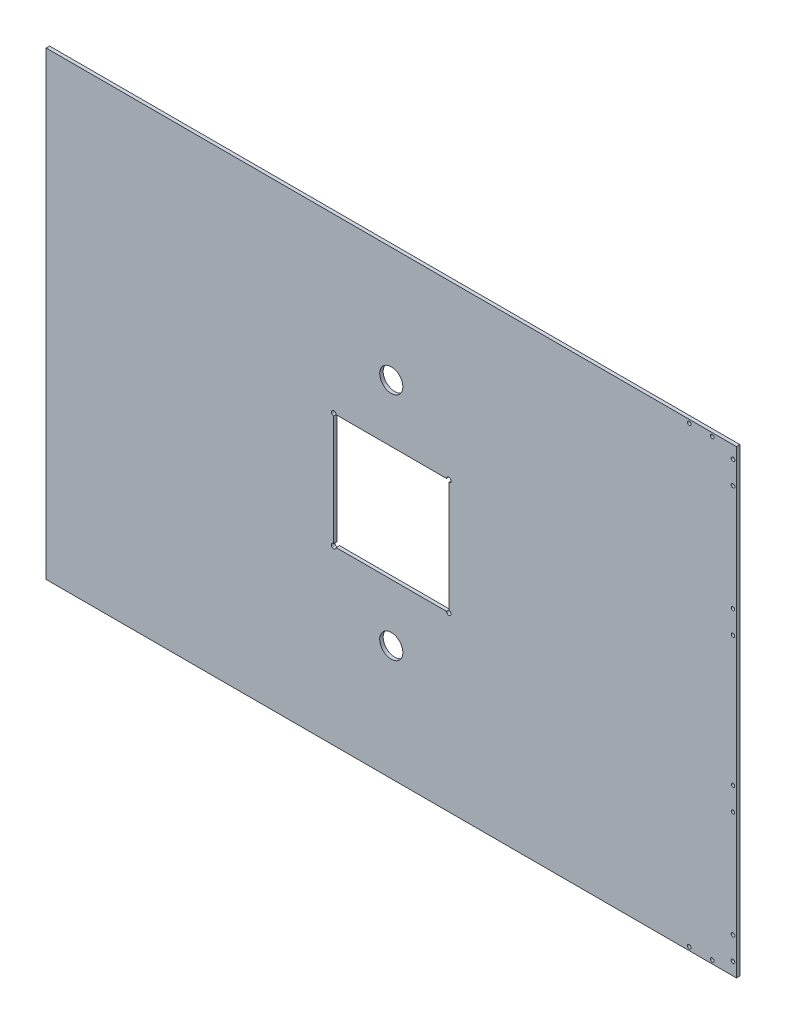
SolidWorks part; units mm, degrees
ref_plane "前视基准面" through (0, 0, 0) normal (0, 0, 1) x (1, 0, 0)
ref_plane "上视基准面" through (0, 0, 0) normal (0, 1, 0) x (1, 0, 0)
ref_plane "右视基准面" through (0, 0, 0) normal (1, 0, 0) x (0, 0, -1)
other "Configuration Table"
sketch "草图1" plane through (0, 0, 0) normal (0, 0, 1) x (1, 0, 0)
  line L1 (-300, 200) -> (300, 200)
  line L2 (-300, 200) -> (-300, -200)
  line L3 (-300, -200) -> (300, -200)
  line L4 (300, 200) -> (300, -200)
  line L5 (-300, 200) -> (300, -200) construction
  line L6 (-300, -200) -> (300, 200) construction
  point P0 (0, 0)
  dimension "D1" = 600
  dimension "D2" = 400
extrude "凸台-拉伸1" add sketch "草图1" along normal blind 3
sketch "草图3" plane through (0, 0, 0) normal (0, 0, -1) x (-1, 0, 0)
  line L1 (-50, 50) -> (50, 50)
  line L2 (-50, 50) -> (-50, -50)
  line L3 (-50, -50) -> (50, -50)
  line L4 (50, 50) -> (50, -50)
  line L5 (-50, 50) -> (50, -50) construction
  line L6 (-50, -50) -> (50, 50) construction
  point P0 (0, 0)
  dimension "D1" = 100
extrude "切除-拉伸1" cut sketch "草图3" against normal through all
sketch "草图4" plane through (0, 0, 3) normal (0, 0, 1) x (1, 0, 0)
  circle A0 centre (-50, 50) radius 2
  circle A1 centre (-50, -50) radius 2
  circle A2 centre (50, -50) radius 2
  circle A3 centre (50, 50) radius 2
  dimension "D1" = 4
extrude "切除-拉伸2" cut sketch "草图4" against normal through all
sketch "草图5" plane through (0, 0, 0) normal (0, 0, -1) x (-1, 0, 0)
  line L0 (-300, -200) -> (-300, 200) construction
  line L1 (-300, 200) -> (300, 200) construction
  line L2 (0, 0) -> (-475.2324, 0) construction
  circle A4 centre (-297, 169) radius 1.6
  circle A5 centre (-297, 189) radius 1.6
  circle A6 centre (-279, 197) radius 1.6
  circle A7 centre (-259, 197) radius 1.6
  circle A8 centre (-259, -197) radius 1.6
  circle A9 centre (-279, -197) radius 1.6
  circle A10 centre (-297, -189) radius 1.6
  circle A11 centre (-297, -169) radius 1.6
  dimension "D1" = 3.2
  dimension "D2" = 20
  dimension "D3" = 3
  dimension "D4" = 11
  dimension "D5" = 20
  dimension "D6" = 3
  dimension "D7" = 21
extrude "切除-拉伸3" cut sketch "草图5" against normal through all
sketch "草图6" plane through (0, 0, 0) normal (0, 0, -1) x (-1, 0, 0)
  line L0 (0, 0) -> (368.4024, 0) construction
  circle A0 centre (0, 100) radius 10.05
  circle A2 centre (0, -100) radius 10.05
  dimension "D1" = 20.1
  dimension "D2" = 100
extrude "切除-拉伸4" cut sketch "草图6" against normal through all
sketch "草图7" plane through (0, 0, 0) normal (0, 0, -1) x (-1, 0, 0)
  line L1 (0, 0) -> (-513.5424, 0) construction
  line L2 (-300, -200) -> (-300, 200) construction
  circle A2 centre (-297, -56.5) radius 1.5
  circle A3 centre (-297, -76.5) radius 1.5
  circle A6 centre (-297, 76.5) radius 1.5
  circle A7 centre (-297, 56.5) radius 1.5
  point P4 (-297, -56.5)
  point P5 (0, 0)
  point P12 (-297.0251, -76.5)
  point P17 (0, 0)
  dimension "D1" = 3
  dimension "D2" = 56.5
  dimension "D3" = 20
  dimension "D4" = 3
extrude "切除-拉伸5" cut sketch "草图7" against normal through all
